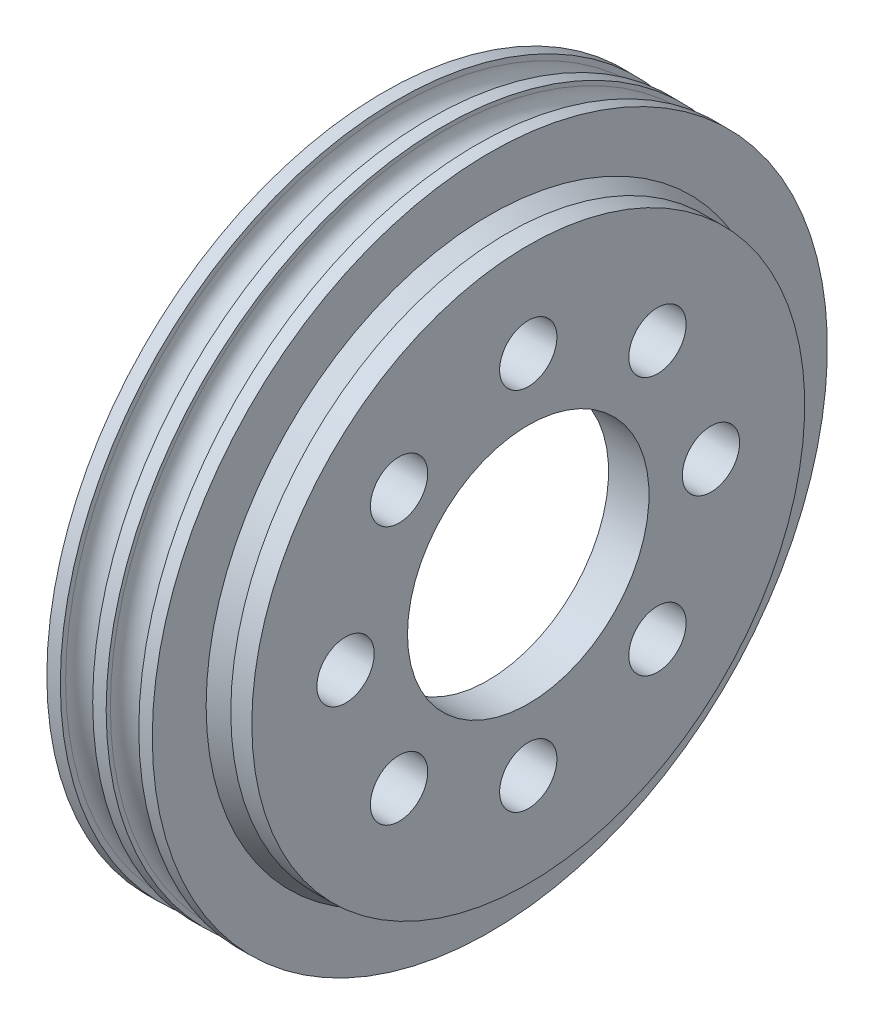
SolidWorks part; units mm, degrees
material "1060 Alloy"
ref_plane "Front Plane" through (0, 0, 0) normal (0, 0, 1) x (1, 0, 0)
ref_plane "Top Plane" through (0, 0, 0) normal (0, 1, 0) x (1, 0, 0)
ref_plane "Right Plane" through (0, 0, 0) normal (1, 0, 0) x (0, 0, -1)
sketch "Sketch1" plane through (0, 0, 0) normal (0, 0, 1) x (1, 0, 0)
  line L0 (1.2561, 4.8317) -> (1.2561, -3.1566)
  line L1 (-14.4439, -1.3284) -> (0.9561, -9.2302)
  line L2 (0.9561, -27.3183) -> (6.9561, -27.3183)
  line L3 (1.2561, -3.1566) -> (3.8359, -4.2302)
  line L4 (0.9561, -27.3183) -> (0.9561, -9.2302)
  line L5 (-14.4439, 4.7698) -> (-12.4439, 4.7698)
  line L6 (-0.7439, 4.8317) -> (-0.7439, 4.1504)
  line L7 (-7.6439, 3.9838) -> (-7.6439, 4.7698)
  line L8 (-5.6439, 4.1504) -> (-5.6439, 4.7698)
  line L9 (-7.6439, 4.7698) -> (-5.6439, 4.7698)
  line L10 (-14.4439, 4.7698) -> (-14.4439, -1.3284)
  line L11 (-12.4439, 4.7698) -> (-12.4439, 3.9838)
  line L12 (-0.7439, 4.8317) -> (1.2561, 4.8317)
  line L13 (-24.7572, -45.2302) -> (67.289, -45.2302) construction
  line L14 (3.8359, -4.2302) -> (6.9561, -4.2302)
  line L16 (6.9561, -27.3183) -> (6.9561, -4.2302)
  arc A0 (-5.6439, 4.1504) -> (-0.7439, 4.1504) centre (-3.1939, 4.1504) ccw
  arc A1 (-7.6439, 3.9838) -> (-12.4439, 3.9838) centre (-10.0439, 3.9838) cw
  point P47 (-14.4439, -1.3284)
  dimension "D6" = 2
  dimension "D7" = 50.0619
  dimension "D10" = 4.8
  dimension "D2" = 50
  dimension "D12" = 6
  dimension "D1" = 21.4
  dimension "D3" = 36
  dimension "D4" = 17.9119
  dimension "D5" = 15.7
  dimension "D8" = 2
  dimension "D9" = 2
  dimension "D11" = 41
revolve "Revolve1" add sketch "Sketch1" angle 360 about L13
sketch "Sketch2" plane through (0.9561, 0, 0) normal (-1, 0, 0) x (0, 0, 1)
  circle A1 centre (0, -18.1302) radius 4.25
  circle A2 centre (19.1626, -26.0676) radius 4.25
  circle A3 centre (27.1, -45.2302) radius 4.25
  circle A4 centre (19.1626, -64.3928) radius 4.25
  circle A5 centre (0, -72.3302) radius 4.25
  circle A6 centre (-19.1626, -64.3928) radius 4.25
  circle A7 centre (-27.1, -45.2302) radius 4.25
  circle A8 centre (-19.1626, -26.0676) radius 4.25
  dimension "D2" = 8.5
extrude "Cut-Extrude1" cut sketch "Sketch2" against normal blind 10
